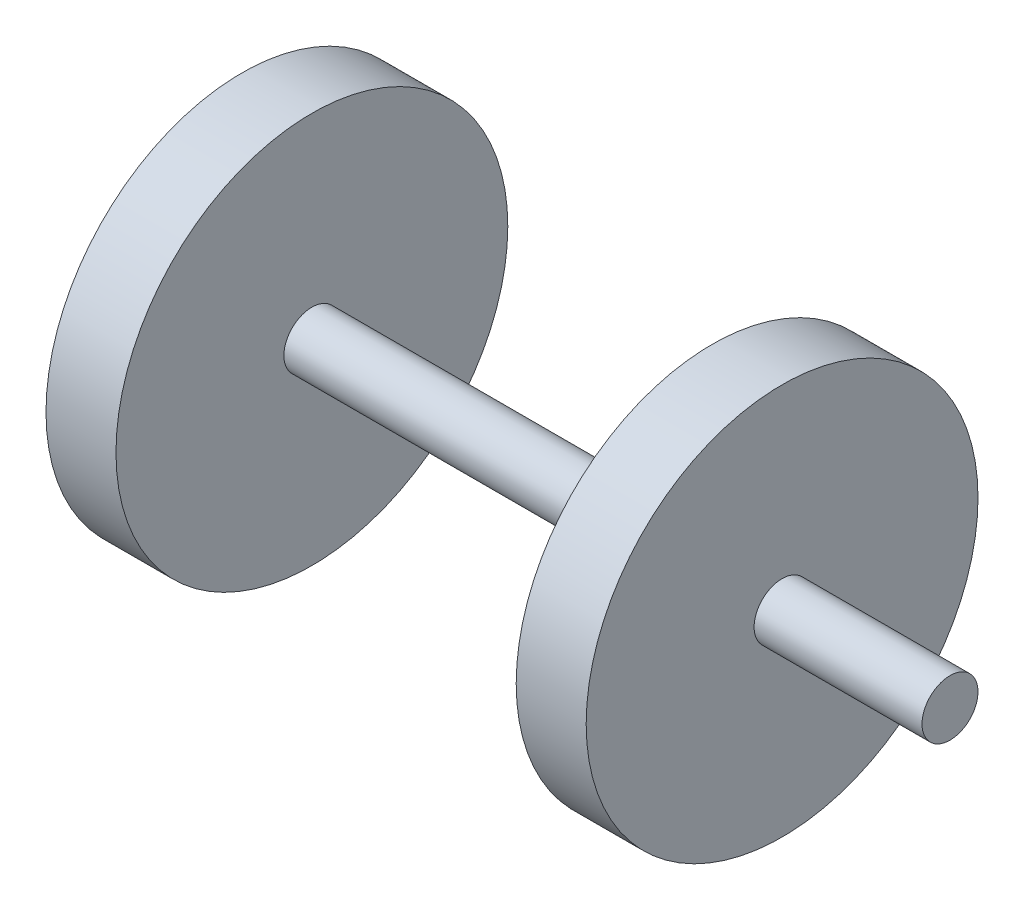
SolidWorks part; units mm, degrees
ref_plane "前视基准面" through (0, 0, 0) normal (0, 0, 1) x (1, 0, 0)
ref_plane "上视基准面" through (0, 0, 0) normal (0, 1, 0) x (1, 0, 0)
ref_plane "右视基准面" through (0, 0, 0) normal (1, 0, 0) x (0, 0, -1)
sketch "草图1" plane through (0, 0, 0) normal (0, 0, 1) x (1, 0, 0)
  line L0 (12.5, 0) -> (84, 0)
  line L1 (0, 0) -> (12.5, 0)
  line L2 (0, 0) -> (0, 35)
  line L3 (0, 35) -> (12.5, 35)
  line L4 (12.5, 5) -> (12.5, 35)
  line L6 (84, 5) -> (12.5, 5)
  line L7 (84, 5) -> (84, 35)
  line L8 (84, 35) -> (96.5, 35)
  line L9 (96.5, 35) -> (96.5, 5)
  line L10 (96.5, 5) -> (126.5, 5)
  line L11 (126.5, 5) -> (126.5, 0)
  line L12 (126.5, 0) -> (84, 0)
  point P11 (0, 0)
revolve "旋转1" add sketch "草图1" angle 360 about L0
